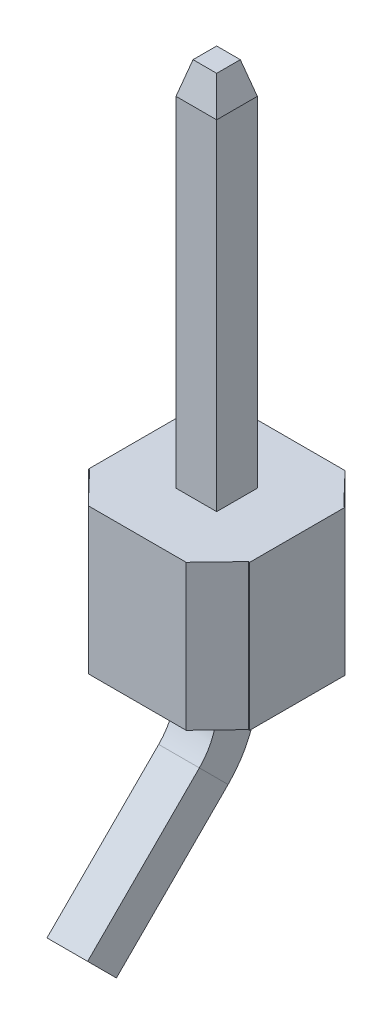
SolidWorks part; units mm, degrees
ref_plane "Front Plane" through (0, 0, 0) normal (0, 0, 1) x (1, 0, 0)
ref_plane "Top Plane" through (0, 0, 0) normal (0, 1, 0) x (1, 0, 0)
ref_plane "Right Plane" through (0, 0, 0) normal (1, 0, 0) x (0, 0, -1)
sketch "Sketch1" plane through (0, 0, 0) normal (0, 1, 0) x (1, 0, 0)
  line L14 (-0.77, 1.25) -> (0.77, 1.25)
  line L20 (-0.77, -1.25) -> (0.77, -1.25)
  line L22 (1.27, -0.75) -> (1.27, 0.75)
  line L23 (1.27, -1.25) -> (-1.27, 1.25) construction
  line L24 (0.77, -1.25) -> (1.25, -0.75)
  line L25 (1.25, -0.75) -> (1.27, -0.75)
  line L26 (0, 0) -> (0, -1.4708) construction
  line L27 (0, 0) -> (1.4893, 0) construction
  line L28 (0.77, 1.25) -> (1.25, 0.75)
  line L29 (1.25, 0.75) -> (1.27, 0.75)
  line L30 (-1.25, 0.75) -> (-1.27, 0.75)
  line L31 (-0.77, 1.25) -> (-1.25, 0.75)
  line L32 (-1.25, -0.75) -> (-1.27, -0.75)
  line L33 (-0.77, -1.25) -> (-1.25, -0.75)
  line L34 (-1.27, -0.75) -> (-1.27, 0.75)
  point P25 (0, 1.25)
  point P29 (0, 0)
  point P38 (1.27, 0)
  point P43 (0, -1.25)
  dimension "D11" = 1.25
  dimension "D12" = 1.27
  dimension "D13" = 0.5
  dimension "D14" = 0.02
  dimension "D15" = 0.5
extrude "Boss-Extrude1" add sketch "Sketch1" along normal blind 2.29
sketch "Sketch2" plane through (0, 0, 0) normal (1, 0, 0) x (0, 0, -1)
  line L0 (0, 8.13) -> (0, -0.4081)
  line L1 (-0.75, 2.29) -> (0.75, 2.29) construction
  line L2 (-0.3661, -1.292) -> (-2.1241, -3.05)
  line L3 (0.75, 0) -> (1.25, 0) construction
  arc A0 (0, -0.4081) -> (-0.3661, -1.292) centre (-1.25, -0.4081) cw
  dimension "D4" = 1.25
  dimension "D1" = 5.84
  dimension "D2" = 135
  dimension "D3" = 3.05
ref_plane "Plane1" through (0, 8.13, 0) normal (0, 1, 0) x (1, 0, 0)
sketch "Sketch3" plane through (0, 8.13, 0) normal (0, 1, 0) x (1, 0, 0)
  line L1 (-0.32, 0.32) -> (0.32, 0.32)
  line L2 (-0.32, 0.32) -> (-0.32, -0.32)
  line L3 (-0.32, -0.32) -> (0.32, -0.32)
  line L4 (0.32, 0.32) -> (0.32, -0.32)
  line L5 (-0.32, 0.32) -> (0.32, -0.32) construction
  line L6 (-0.32, -0.32) -> (0.32, 0.32) construction
  point P0 (0, 0)
  dimension "D1" = 0.64
sweep "Sweep1" add profiles "Sketch3" path "Sketch2"
chamfer "Chamfer3" distance 0.5 angle 15 4 edges at (0, 8.13, 0.32) (-0.32, 8.13, 0) (0, 8.13, -0.32) (0.32, 8.13, 0)
